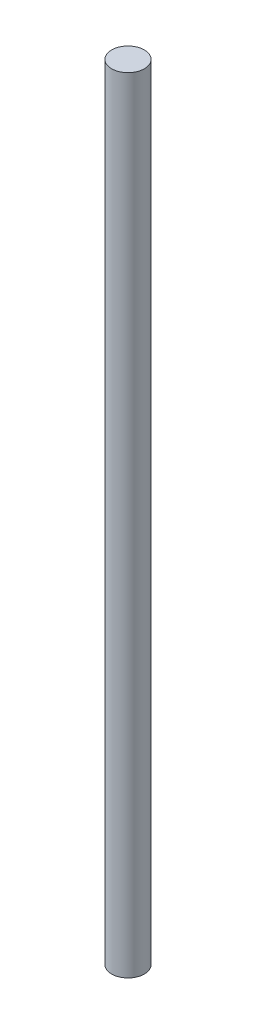
SolidWorks part; units mm, degrees
ref_plane "Front Plane" through (0, 0, 0) normal (0, 0, 1) x (1, 0, 0)
ref_plane "Top Plane" through (0, 0, 0) normal (0, 1, 0) x (1, 0, 0)
ref_plane "Right Plane" through (0, 0, 0) normal (1, 0, 0) x (0, 0, -1)
sketch "Sketch1" plane through (0, 0, 0) normal (0, 1, 0) x (1, 0, 0)
  circle A0 centre (0, 0) radius 25.4
  dimension "D1" = 50.8
extrude "Boss-Extrude1" add sketch "Sketch1" along normal blind 1219.2
